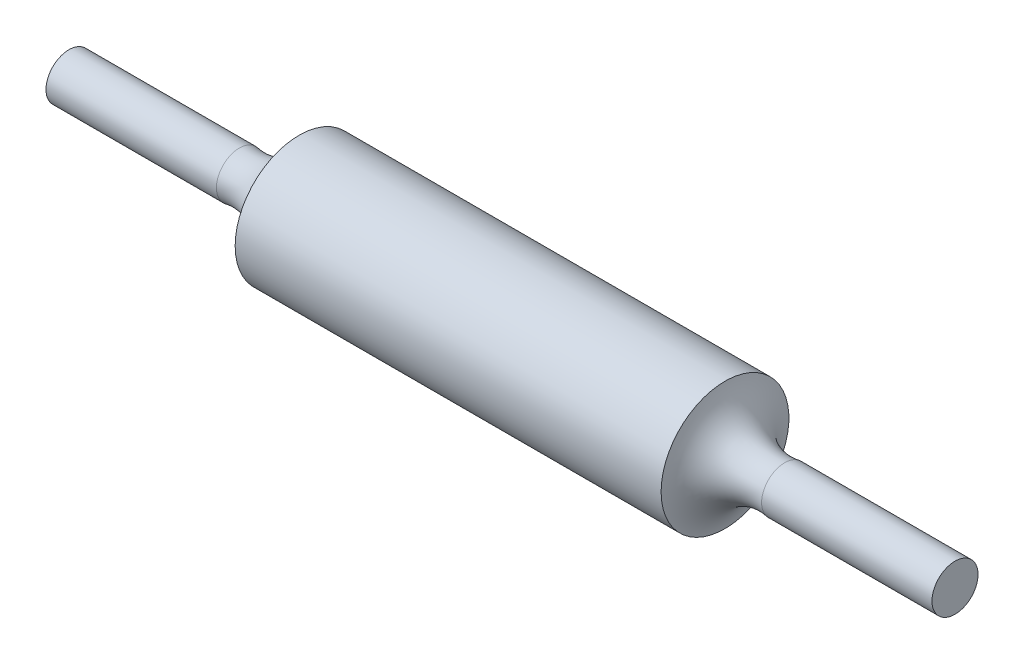
SolidWorks part; units mm, degrees
material "Cobre-berílio, UNS C17000"
ref_plane "Plano frontal" through (0, 0, 0) normal (0, 0, 1) x (1, 0, 0)
ref_plane "Plano superior" through (0, 0, 0) normal (0, 1, 0) x (1, 0, 0)
ref_plane "Plano direito" through (0, 0, 0) normal (1, 0, 0) x (0, 0, -1)
sketch "Esboço1" plane through (0, 0, 0) normal (0, 1, 0) x (1, 0, 0)
  line L0 (-4.5, 0) -> (4.5, 0) construction
  line L1 (-25, -7.5) -> (25, -7.5)
  line L2 (-52, -2.7042) -> (-32, -2.7042)
  line L3 (52, -2.7042) -> (32, -2.7042)
  line L4 (0, 4.0193) -> (0, -5.9751) construction
  line L5 (52, -2.7042) -> (52, 0)
  line L6 (52, 0) -> (-52, 0)
  line L7 (-52, 0) -> (-52, -2.7042)
  arc A2 (-25, -7.5) -> (-32, -2.7042) centre (-30.8979, -8.6021) ccw
  arc A3 (32, -2.7042) -> (25, -7.5) centre (30.8979, -8.6021) ccw
  point P10 (0, -7.5)
  dimension "D3" = 6
  dimension "D5" = 7
  dimension "D7" = 104
  dimension "D6" = 20
  dimension "D4" = 90
  dimension "D1" = 50
  dimension "D2" = 7.5
revolve "Revolução1" add sketch "Esboço1" angle 360 about L0
